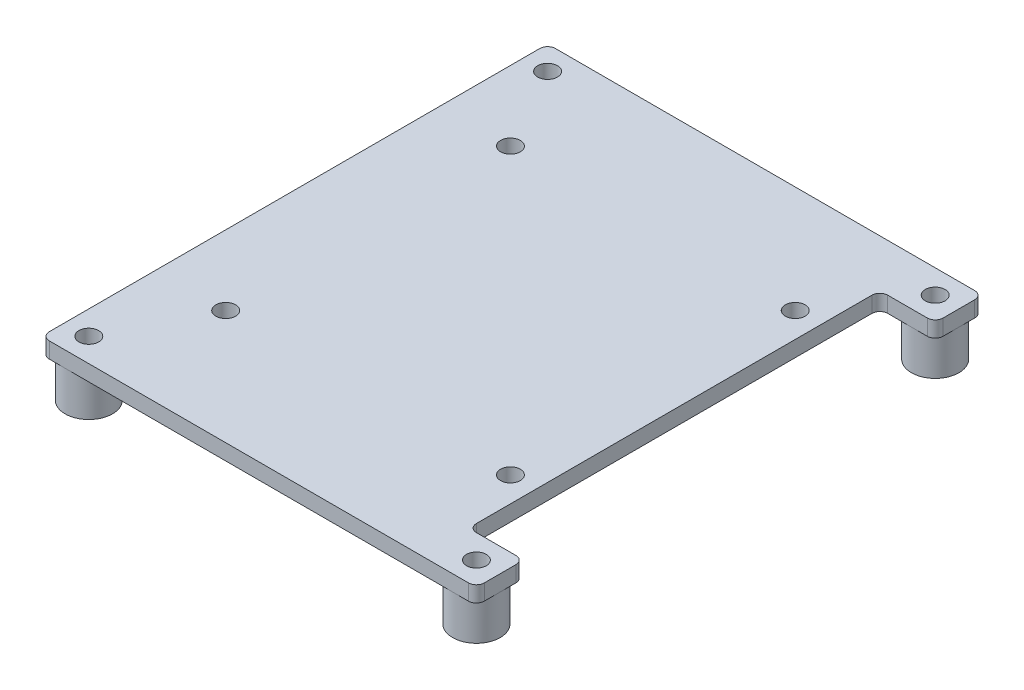
SolidWorks part; units mm, degrees
material "ABS"
ref_plane "Front Plane" through (0, 0, 0) normal (0, 0, 1) x (1, 0, 0)
ref_plane "Top Plane" through (0, 0, 0) normal (0, 1, 0) x (1, 0, 0)
ref_plane "Right Plane" through (0, 0, 0) normal (1, 0, 0) x (0, 0, -1)
other "Configuration Table"
sketch "Sketch2" plane through (0, 0, 0) normal (0, 1, 0) x (1, 0, 0)
  line L0 (-5.8302, 10.5288) -> (-5.8302, -47.4712) construction
  line L1 (-8.8302, 13.5288) -> (46.1698, 13.5288)
  line L2 (-5.8302, 10.5288) -> (43.1698, 10.5288)
  line L3 (-5.8302, 10.5288) -> (-5.8302, -47.4712)
  line L4 (-5.8302, -47.4712) -> (43.1698, -47.4712)
  line L5 (43.1698, 10.5288) -> (43.1698, -47.4712)
  line L6 (46.1698, 13.5288) -> (46.1698, -50.4712)
  line L7 (-8.8302, -50.4712) -> (46.1698, -50.4712)
  line L8 (-8.8302, 13.5288) -> (-8.8302, -50.4712)
  circle B0 centre (-5.8302, -47.4712) radius 1.25
  circle B1 centre (43.1698, -47.4712) radius 1.25
  circle B2 centre (43.1698, 10.5288) radius 1.25
  circle B3 centre (-5.8302, 10.5288) radius 1.25
  arc B4 (-1.2499, 0) -> (1.2499, 0) centre (0, 0) ccw
  arc B5 (1.2499, 0) -> (-1.2499, 0) centre (0, 0) ccw
  arc B6 (34.75, 0) -> (37.2499, 0) centre (35.9999, 0) ccw
  arc B7 (37.2499, 0) -> (34.75, 0) centre (35.9999, 0) ccw
  arc B8 (-1.2499, -35.9999) -> (1.2499, -35.9999) centre (0, -35.9999) ccw
  arc B9 (1.2499, -35.9999) -> (-1.2499, -35.9999) centre (0, -35.9999) ccw
  arc B10 (34.75, -35.9999) -> (37.2499, -35.9999) centre (35.9999, -35.9999) ccw
  arc B11 (37.2499, -35.9999) -> (34.75, -35.9999) centre (35.9999, -35.9999) ccw
  dimension "D1" = 3
sketch_block_instance "Block3-1"
sketch_block "Block3" parameters "D1"=2.7
extrude "Boss-Extrude1" add sketch "Sketch2" along normal blind 2 contours L1 L8 L7 L6 B3 L2 B2 L5 B1 L4 B0 L3 | B3 L3 B0 L4 B1 L5 B2 L2 B11 B10 B9 B8 B7 B6 B5 B4
sketch "Sketch4" plane through (0, 2, 0) normal (0, 1, 0) x (1, 0, 0)
  line L0 (46.1698, 13.5288) -> (46.1698, -50.4712) construction
  line L1 (46.1698, 7.5288) -> (39.1698, 7.5288)
  line L2 (46.1698, 7.5288) -> (46.1698, -44.4712)
  line L3 (46.1698, -44.4712) -> (39.1698, -44.4712)
  line L4 (39.1698, 7.5288) -> (39.1698, -44.4712)
  point P6 (46.1698, 13.5288)
  point P7 (46.1698, -50.4712)
  dimension "D1" = 6
  dimension "D2" = 6
  dimension "D3" = 7
extrude "Cut-Extrude1" cut sketch "Sketch4" against normal blind 2
fillet "Fillet1" radius 1 8 edges at (46.1698, 1, -7.5288) (46.1698, 1, -13.5288) (-8.8302, 1, -13.5288) (-8.8302, 1, 50.4712) (46.1698, 1, 50.4712) (46.1698, 1, 44.4712) (39.1698, 1, 44.4712) (39.1698, 1, -7.5288)
sketch "Sketch5" plane through (0, 2, 0) normal (0, 1, 0) x (1, 0, 0)
  circle A0 centre (-5.8302, 10.5288) radius 3
  circle A1 centre (43.1698, 10.5288) radius 3
  circle A2 centre (43.1698, -47.4712) radius 3
  circle A3 centre (-5.8302, -47.4712) radius 3
  circle A4 centre (-5.8302, -47.4712) radius 1.25 construction
  circle A5 centre (-5.8302, 10.5288) radius 1.25 construction
  circle A6 centre (43.1698, 10.5288) radius 1.25 construction
  circle A7 centre (43.1698, -47.4712) radius 1.25 construction
  circle A8 centre (-5.8302, -47.4712) radius 1.25
  circle A9 centre (-5.8302, 10.5288) radius 1.25
  circle A10 centre (43.1698, 10.5288) radius 1.25
  circle A11 centre (43.1698, -47.4712) radius 1.25
extrude "Boss-Extrude2" add sketch "Sketch5" against normal blind 7
sketch "Sketch6" plane through (0, 0, 0) normal (0, -1, 0) x (1, 0, 0)
  line L0 (39.1698, -6.5288) -> (39.1698, 43.4712) construction
  line L1 (-3.8302, 29.6174) -> (34.1698, 29.6174)
  line L2 (-3.8302, 29.6174) -> (-3.8302, 6.1199)
  line L3 (-3.8302, 6.1199) -> (34.1698, 6.1199)
  line L4 (34.1698, 29.6174) -> (34.1698, 6.1199)
  line L5 (7.4291, 45.4712) -> (28.14, 45.4712)
  line L6 (7.4291, 45.4712) -> (7.4291, -8.5288)
  line L7 (7.4291, -8.5288) -> (28.14, -8.5288)
  line L8 (28.14, 45.4712) -> (28.14, -8.5288)
  line L9 (-8.8302, -10.5288) -> (-8.8302, 47.4712) construction
  line L10 (-5.8302, 50.4712) -> (43.1698, 50.4712) construction
  line L11 (-5.8302, -13.5288) -> (43.1698, -13.5288) construction
  dimension "D1" = 5
  dimension "D2" = 5
  dimension "D3" = 5
  dimension "D4" = 5
extrude "Cut-Extrude2" [suppressed] cut sketch "Sketch6" against normal blind 7 contours L8 L5 L6 L1 | L8 L1 L6 L3 | L1 L8 L3 L4 | L8 L3 L6 L7 | L6 L1 L2 L3
sketch "Sketch8" [suppressed] plane through (0, 0, 0) normal (0, -1, 0) x (1, 0, 0)
  line L0 (28.605, 45.8519) -> (7.4291, -8.5288)
  line L1 (7.4291, 6.1199) -> (7.4291, -8.5288) construction
  line L2 (7.4291, 45.4712) -> (28.14, -8.5288)
  line L3 (-4.2124, 6.2835) -> (34.1698, 29.6174)
  line L4 (-3.8302, 29.6174) -> (34.1698, 6.1199)
  point P15 (7.4291, -8.5288)
extrude "Extrude-Thin1" [suppressed] add sketch "Sketch8" against normal up to surface (2 mm away) thin
